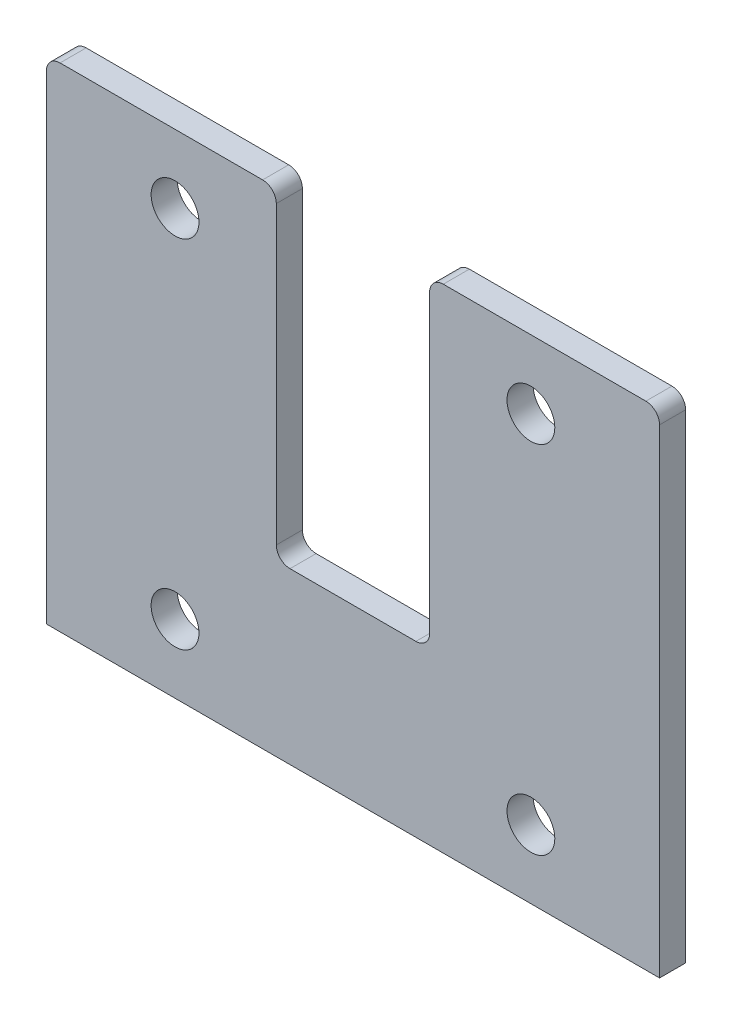
SolidWorks part; units mm, degrees
ref_plane "Alzado" through (0, 0, 0) normal (0, 0, 1) x (1, 0, 0)
ref_plane "Planta" through (0, 0, 0) normal (0, 1, 0) x (1, 0, 0)
ref_plane "Vista lateral" through (0, 0, 0) normal (1, 0, 0) x (0, 0, -1)
sketch "Croquis1" plane through (0, 0, 0) normal (0, 0, 1) x (1, 0, 0)
  line L1 (0, 0) -> (224, 0)
  line L2 (0, 0) -> (0, -180)
  line L3 (0, -180) -> (224, -180)
  line L4 (224, 0) -> (224, -180)
  dimension "D1" = 224
  dimension "D2" = 180
extrude "Saliente-Extruir1" add sketch "Croquis1" along normal blind 9.525
sketch "Croquis2" plane through (0, 0, 9.525) normal (0, 0, 1) x (1, 0, 0)
  line L0 (112, 0) -> (112, -90) construction
  line L1 (224, 0) -> (0, 0) construction
  line L2 (84, 0) -> (84, -118)
  line L3 (84, -118) -> (140, -118)
  line L4 (140, -118) -> (140, 0)
  line L5 (140, 0) -> (112, 0)
  line L6 (112, 0) -> (84, 0)
  line L7 (224, -90) -> (112, -90) construction
  line L8 (224, -180) -> (224, 0) construction
  dimension "D1" = 28
  dimension "D2" = 28
  dimension "D3" = 28
extrude "Cortar-Extruir1" cut sketch "Croquis2" against normal blind 12.7
fillet "Redondeo1" radius 5 6 edges at (140, 0, 4.7625) (84, 0, 4.7625) (84, -118, 4.7625) (140, -118, 4.7625) (224, 0, 4.7625) (0, 0, 4.7625)
sketch "Croquis3" plane through (0, 0, 9.525) normal (0, 0, 1) x (1, 0, 0)
  line L0 (0, 0) -> (0, -180) construction
  line L2 (0, -90) -> (112, -90) construction
  line L5 (0, -180) -> (224, -180) construction
  line L6 (112, -180) -> (112, -90) construction
  line L7 (112, -90) -> (112, -25) construction
  line L8 (112, -25) -> (177, -25) construction
  line L9 (112, -155) -> (177, -155) construction
  circle A0 centre (177, -25) radius 8.7313
  circle A1 centre (47, -25) radius 8.7313
  circle A2 centre (47, -155) radius 8.7312
  circle A3 centre (177, -155) radius 8.7312
  dimension "D3" = 17.4625
  dimension "D1" = 65
  dimension "D2" = 65
extrude "Cortar-Extruir2" cut sketch "Croquis3" against normal blind 13
